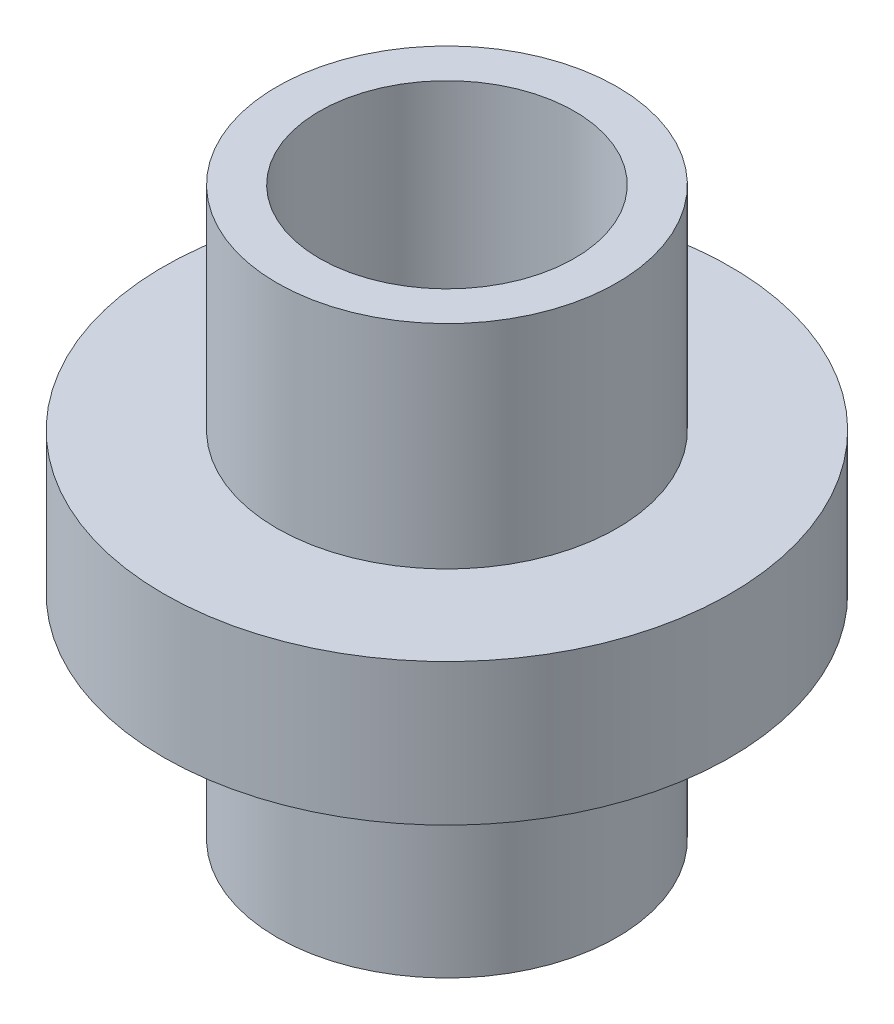
SolidWorks part; units mm, degrees
ref_plane "Front Plane" through (0, 0, 0) normal (0, 0, 1) x (1, 0, 0)
ref_plane "Top Plane" through (0, 0, 0) normal (0, 1, 0) x (1, 0, 0)
ref_plane "Right Plane" through (0, 0, 0) normal (1, 0, 0) x (0, 0, -1)
sketch "Sketch1" plane through (0, 0, 0) normal (0, 0, 1) x (1, 0, 0)
  line L0 (4.5, 10) -> (6, 10)
  line L1 (6, 10) -> (6, 2.5)
  line L2 (6, 2.5) -> (10, 2.5)
  line L3 (10, 2.5) -> (10, -2.5)
  line L4 (10, -2.5) -> (6, -2.5)
  line L5 (6, -2.5) -> (6, -10)
  line L6 (6, -10) -> (4.5, -10)
  line L7 (4.5, -10) -> (4.5, 10)
  line L8 (0, 10) -> (0, -10) construction
  line L9 (0, -10) -> (4.5, -10) construction
  line L10 (0, 10) -> (4.5, 10) construction
  point P9 (10, 0)
  point P10 (4.5, 0)
  dimension "D1" = 20
  dimension "D2" = 5
  dimension "D3" = 9
  dimension "D4" = 12
  dimension "D5" = 20
revolve "Revolve1" add sketch "Sketch1" angle 360 about L8
